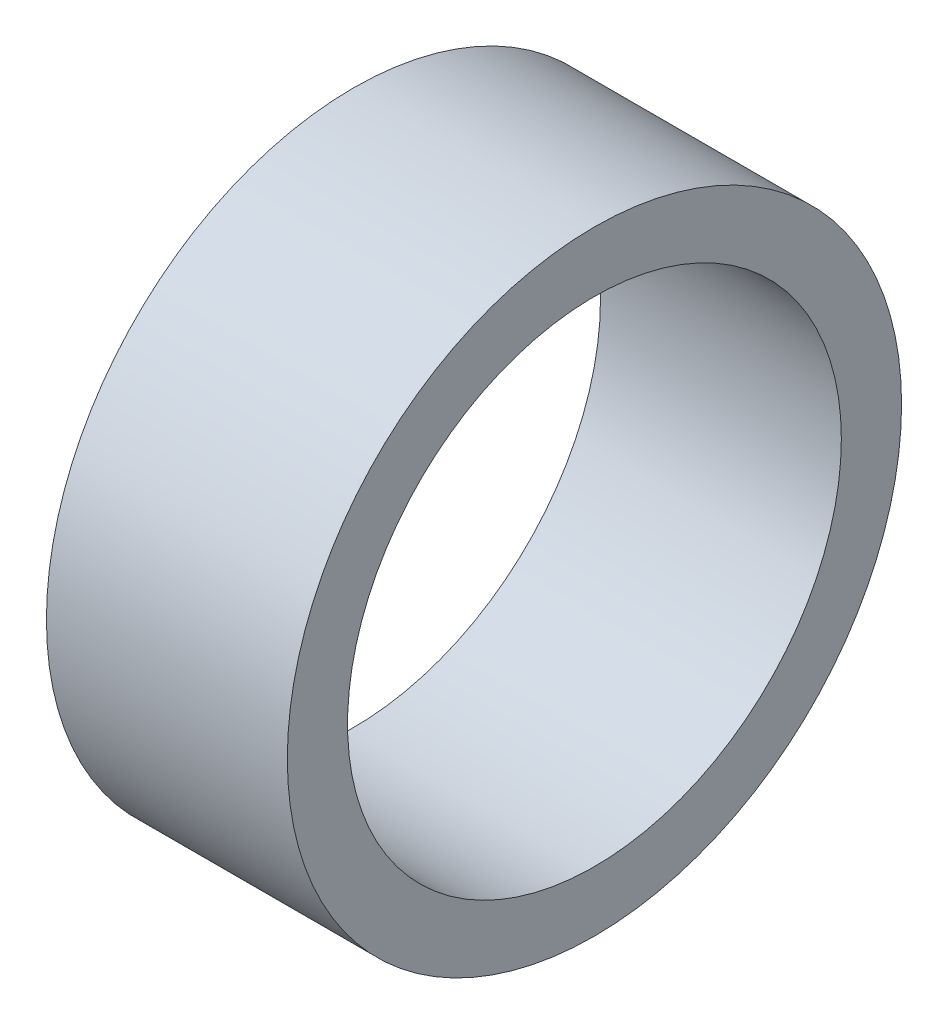
SolidWorks part; units mm, degrees
ref_plane "Vorne" through (0, 0, 0) normal (0, 0, 1) x (1, 0, 0)
ref_plane "Oben" through (0, 0, 0) normal (0, 1, 0) x (1, 0, 0)
ref_plane "Seite" through (0, 0, 0) normal (1, 0, 0) x (0, 0, -1)
sketch "Skizze1" plane through (0, 0, 0) normal (1, 0, 0) x (0, 0, -1)
  circle A0 centre (0, 0) radius 2.05
  circle A1 centre (0, 0) radius 2.55
  dimension "D1" = 4.1
  dimension "D2" = 5.1
extrude "Aufsatz-Linear austragen1" add sketch "Skizze1" along normal blind 2
